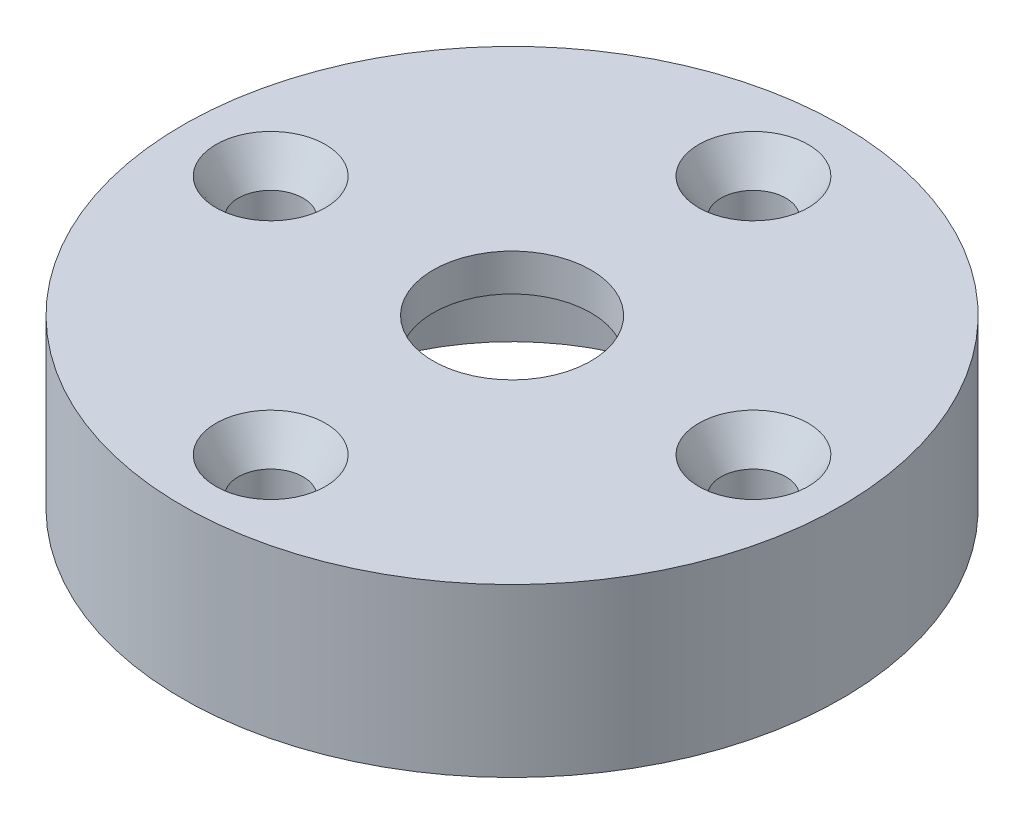
SolidWorks part; units mm, degrees
ref_plane "Front Plane" through (0, 0, 0) normal (0, 0, 1) x (1, 0, 0)
ref_plane "Top Plane" through (0, 0, 0) normal (0, 1, 0) x (1, 0, 0)
ref_plane "Right Plane" through (0, 0, 0) normal (1, 0, 0) x (0, 0, -1)
sketch "Sketch3" plane through (0, 0, 0) normal (0, 0, 1) x (1, 0, 0)
  line L0 (0, 0) -> (0, 34.5832) construction
  line L1 (-11, 0) -> (-17.75, 0)
  line L2 (-17.75, 0) -> (-17.75, 9)
  line L3 (-17.75, 9) -> (-4.25, 9)
  line L4 (-4.25, 9) -> (-4.25, 7)
  line L5 (-4.25, 7) -> (-11, 7)
  line L6 (-11, 7) -> (-11, 0)
  dimension "D1" = 35.5
  dimension "D2" = 7
  dimension "D3" = 22
  dimension "D4" = 8.5
  dimension "D5" = 2
revolve "Revolve1" add sketch "Sketch3" angle 360 about L0
sketch "Sketch4" plane through (0, 9, 0) normal (0, 1, 0) x (1, 0, 0)
  circle A0 centre (0, 0) radius 13 construction
  circle A1 centre (0, 13) radius 1.75
  circle A2 centre (13, 0) radius 1.75
  circle A3 centre (0, -13) radius 1.75
  circle A4 centre (-13, 0) radius 1.75
  point P14 (0, 0)
  dimension "D1" = 26
  dimension "D2" = 3.5
  dimension "D3" = 4
extrude "Cut-Extrude1" cut sketch "Sketch4" against normal up to surface (9 mm away) up to face at (0, 0, -11)
chamfer "Chamfer1" distance 1.2 distance2 1.9 4 edges at (0, 9, 14.75) (13, 9, 1.75) (0, 9, -11.25) (-13, 9, 1.75)
